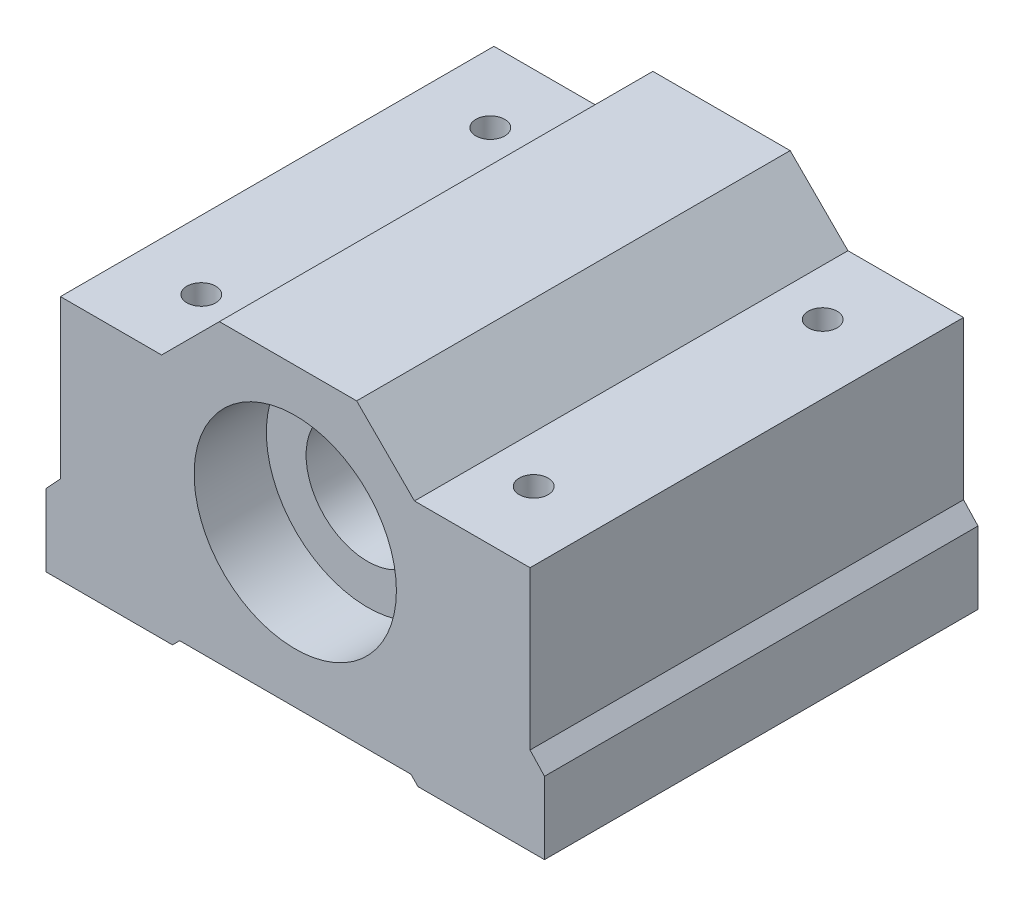
SolidWorks part; units mm, degrees
ref_plane "Front Plane" through (0, 0, 0) normal (0, 0, 1) x (1, 0, 0)
ref_plane "Top Plane" through (0, 0, 0) normal (0, 1, 0) x (1, 0, 0)
ref_plane "Right Plane" through (0, 0, 0) normal (1, 0, 0) x (0, 0, -1)
sketch "Sketch1" plane through (0, 0, 0) normal (0, 0, 1) x (1, 0, 0)
  line L0 (8, -10) -> (-8, -10)
  line L1 (-17.25, -10.5) -> (-9, -10.5)
  line L2 (-17.25, -10.5) -> (-17.25, -5.5)
  line L3 (-5.25, 10.5) -> (4.25, 10.5)
  line L4 (17.25, -10.5) -> (17.25, -5.5)
  line L5 (-17.25, -10.5) -> (10.6786, 6.5) construction
  line L6 (-10.6786, 6.5) -> (17.25, -10.5) construction
  line L9 (8.5, -10.5) -> (17.25, -10.5)
  line L10 (17.25, -10.5) -> (17.25, -5.5)
  line L11 (17.25, -5.5) -> (16.25, -4.4272)
  line L12 (16.25, -4.4272) -> (16.25, 6.5)
  line L13 (8, -10) -> (8.5, -10.5)
  line L14 (-8, -10) -> (-8.5, -10.5)
  line L15 (-9, -10.5) -> (-8.5, -10.5)
  line L16 (-16.25, 6.5) -> (16.25, 6.5)
  line L17 (16.25, 6.5) -> (8.25, 6.5)
  line L18 (8.25, 6.5) -> (4.25, 10.5)
  line L19 (-9.25, 6.5) -> (-5.25, 10.5)
  line L20 (0, 14.1044) -> (0, -11.9536) construction
  line L21 (-17.25, -5.5) -> (-16.25, -4.4272)
  line L22 (-16.25, -4.4272) -> (-16.25, 6.5)
  line L23 (-16.25, 6.5) -> (-9.25, 6.5)
  circle A1 centre (0, 0.5) radius 7
  point P0 (0, 0)
  point P9 (0, -10)
  dimension "D2" = 14
  dimension "D12" = 10
  dimension "D3" = 0.5
  dimension "D4" = 16
  dimension "D5" = 0
  dimension "D6" = 5
  dimension "D7" = 1
  dimension "D8" = 4
  dimension "D9" = 8
  dimension "D10" = 8
  dimension "D11" = 10.5
extrude "Boss-Extrude1" add sketch "Sketch1" along normal blind 30 contours A1 L16 L22 L21 L2 L1 L15 L14 L0 L13 L9 L4 L11 L12 | A1 L16 L18 L3 L19
sketch "Sketch3" plane through (0, 0, 30) normal (0, 0, 1) x (1, 0, 0)
  circle A4 centre (0, 0.5) radius 7
  circle A5 centre (0, 0.5) radius 7
  circle A6 centre (0, 0.5) radius 4.25
  dimension "D2" = 8.5
  dimension "D1" = 0
extrude "Boss-Extrude2" add sketch "Sketch3" against normal blind 20 from offset 5 offset against normal yes
hole_wizard "Ø2.0mm Dowel Hole1" positions "Sketch4" profile "Sketch5" hole size "Ø2.0" standard "ANSI Metric" end condition through all
sketch "Sketch4" plane through (0, -10.5, 0) normal (0, -1, 0) x (-1, 0, 0)
  line L0 (17.25, -30) -> (8.5, -30) construction
  line L1 (17.25, 0) -> (8.5, 0) construction
  line L2 (0, -30.5575) -> (0, 2.2308) construction
  point P0 (11.5, -25)
  point P2 (11.5, -5)
  point P17 (-11.5, -5)
  point P18 (-11.5, -25)
  dimension "D1" = 5
  dimension "D2" = 5
  dimension "D3" = 11.5
  dimension "D4" = 11.5
sketch "Sketch5" plane through (-11.5, -10.5, 25) normal (1, 0, 0) x (0, 0, -1)
  line L0 (0, 0) -> (0, 21)
  line L1 (0, 21) -> (1, 21)
  line L2 (1, 21) -> (1, 0)
  line L5 (1, 0) -> (0, 0)
  line L11 (0, -6.35) -> (0, 107.95) construction
  dimension "Thru Hole Dia." = 2
  dimension "Thru Hole Depth" = 21
